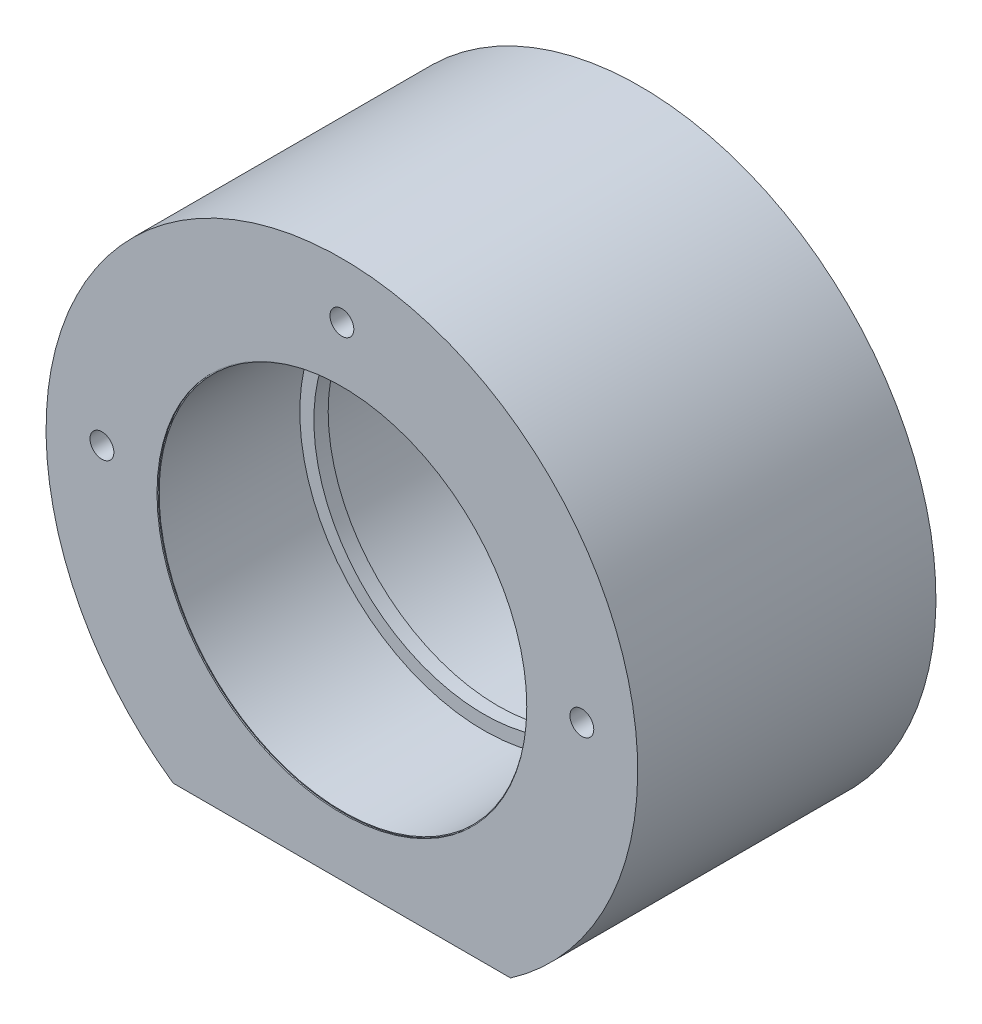
SolidWorks part; units mm, degrees
material "6061 Alloy"
ref_plane "Front Plane" through (0, 0, 0) normal (0, 0, 1) x (1, 0, 0)
ref_plane "Top Plane" through (0, 0, 0) normal (0, 1, 0) x (1, 0, 0)
ref_plane "Right Plane" through (0, 0, 0) normal (1, 0, 0) x (0, 0, -1)
sketch "Sketch1" plane through (0, 0, 0) normal (0, 0, 1) x (1, 0, 0)
  line L0 (-15.9687, 0) -> (15.9687, 0)
  arc A0 (15.9687, 0) -> (-15.9687, 0) centre (0, 23) ccw
  circle A1 centre (0, 23) radius 16.5
  dimension "D2" = 56
  dimension "D3" = 33
  dimension "D1" = 23
extrude "Boss-Extrude1" add sketch "Sketch1" along normal blind 50
sketch "Sketch2" plane through (0, 0, 50) normal (0, 0, 1) x (1, 0, 0)
  circle A0 centre (0, 23) radius 17.5
  arc A1 (15.9687, 0) -> (-15.9687, 0) centre (0, 23) ccw construction
  dimension "D1" = 35
extrude "Cut-Extrude1" cut sketch "Sketch2" against normal blind 11
ref_plane "Plane1" through (0, 0, 25) normal (0, 0, 1) x (1, 0, 0)
mirror "Mirror1" about plane through (0, 0, 25) normal (0, 0, 1) of "Cut-Extrude1"
sketch "Sketch3" plane through (0, 0, 0) normal (0, 0, -1) x (-1, 0, 0)
  circle A0 centre (0, 23) radius 16.5 construction
  circle A1 centre (0, 45.5) radius 2
  circle A2 centre (-22.5, 23) radius 2
  circle A3 centre (22.5, 23) radius 2
  point P0 (0, 23)
  dimension "D4" = 4
  dimension "D1" = 22.5
  dimension "D2" = 22.5
  dimension "D3" = 22.5
extrude "Cut-Extrude2" cut sketch "Sketch3" against normal blind 10
mirror "Mirror2" about plane through (0, 0, 25) normal (0, 0, 1) of "Cut-Extrude2"
scale "Scale1" scale about centroid uniform scaling yes scale factor 1.771429
sketch "Sketch4" plane through (0, 0, 49.8) normal (0, 0, 1) x (1, 0, 0)
  circle A0 centre (0, 21.6035) radius 28.4986
  circle A1 centre (0, 21.6035) radius 29.2286 construction
  circle A2 centre (0, 21.6035) radius 29.2286
  dimension "D1" = 0.73
extrude "Boss-Extrude2" add sketch "Sketch4" against normal up to surface (49.6 mm away) up to face at (-29.2286, 21.6035, 0.2)
ref_plane "Plane3" through (0, 0, 25) normal (0, 0, 1) x (1, 0, 0)
sketch "Sketch6" plane through (0, 0, 25) normal (0, 0, 1) x (1, 0, 0)
  line L0 (-28.2874, -19.1394) -> (28.2874, -19.1394) construction
  line L1 (-28.2874, -19.1394) -> (28.2874, -19.1394)
  circle A0 centre (0, 21.6035) radius 28.4986 construction
  circle A1 centre (0, 21.6035) radius 28.4986
  arc A2 (28.2874, -19.1394) -> (-28.2874, -19.1394) centre (0, 21.6035) ccw construction
  arc A3 (28.2874, -19.1394) -> (-28.2874, -19.1394) centre (0, 21.6035) ccw
extrude "Cut-Extrude6" cut sketch "Sketch6" along normal blind 19.285 from surface at -44.2857 starting at face at (-3.5429, 61.4606, -19.2857)
sketch "Sketch7" plane through (0, 0, 0) normal (0, 0, 1) x (1, 0, 0)
  line L1 (-28.2874, -19.1394) -> (28.2874, -19.1394)
  circle A1 centre (0, 21.6035) radius 28.4986
  arc A3 (28.2874, -19.1394) -> (-28.2874, -19.1394) centre (0, 21.6035) ccw
extrude "Cut-Extrude7" cut sketch "Sketch7" against normal blind 19.285 from surface at 69.2857 starting at face at (-3.5429, 61.4606, 69.2857)
sketch "Sketch9" plane through (0, 0, 50.0007) normal (0, 0, 1) x (1, 0, 0)
  circle A3 centre (0, 21.6035) radius 30.85
  dimension "D1" = 61.7
extrude "Cut-Extrude8" cut sketch "Sketch9" against normal blind 23.8
mirror "Mirror3" about plane through (0, 0, 25) normal (0, 0, 1) of "Cut-Extrude8"
sketch "Sketch10" plane through (0, 0, 50.0007) normal (0, 0, 1) x (1, 0, 0)
  circle A0 centre (0, 61.9035) radius 2
  circle A1 centre (-40.2334, 23.9194) radius 2
  circle A2 centre (40.2334, 23.9194) radius 2
  circle A3 centre (0, 21.6035) radius 40.3
  point P9 (0, 0)
  point P10 (0, 0)
  point P11 (0, 0)
  dimension "D1" = 4
  dimension "D2" = 4
  dimension "D3" = 4
  dimension "D4" = 80.6
extrude "Cut-Extrude9" cut sketch "Sketch10" against normal up to surface (50.0014 mm away) contours A0 A3 | A2 | A1
